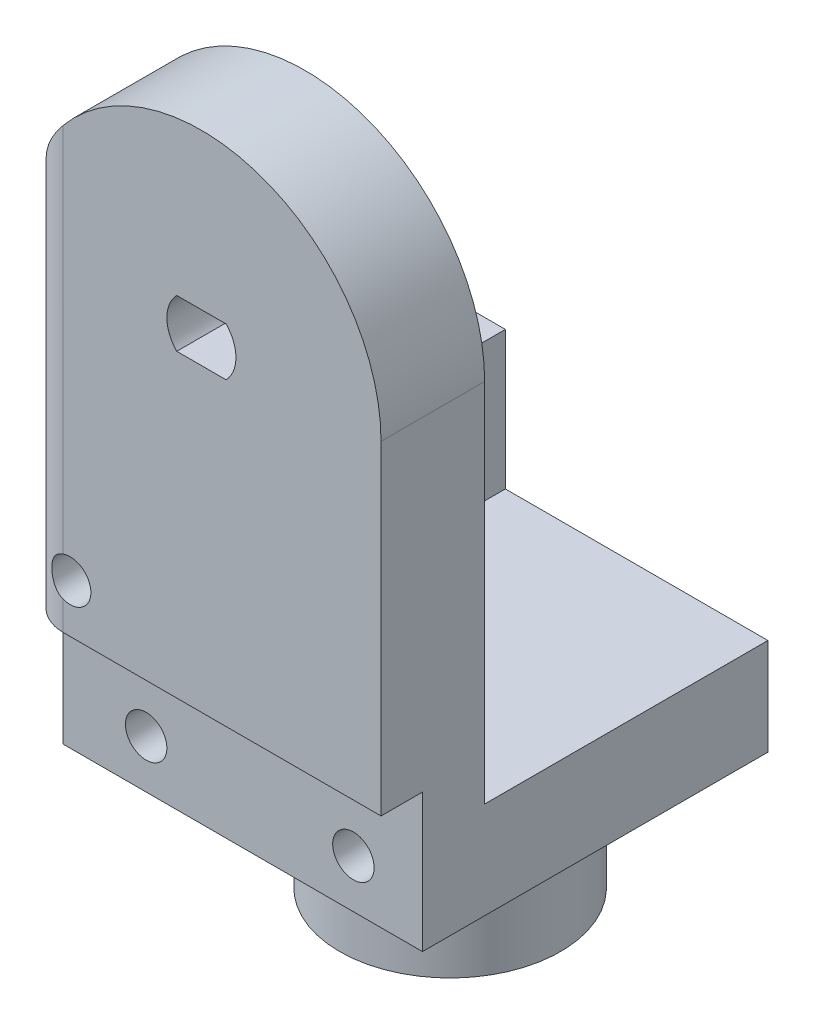
SolidWorks part; units mm, degrees
ref_plane "Front Plane" through (0, 0, 0) normal (0, 0, 1) x (1, 0, 0)
ref_plane "Top Plane" through (0, 0, 0) normal (0, 1, 0) x (1, 0, 0)
ref_plane "Right Plane" through (0, 0, 0) normal (1, 0, 0) x (0, 0, -1)
sketch "Sketch1" plane through (0, 0, 0) normal (0, 0, 1) x (1, 0, 0)
  line L7 (24.2641, -54) -> (50.2641, -54)
  line L9 (24.2641, -4) -> (50.2641, -4)
  line L10 (24.2641, -54) -> (24.2641, -4)
  line L11 (50.2641, -54) -> (50.2641, -4)
  line L14 (39.0495, -22.266) -> (35.4787, -22.266)
  line L15 (35.4787, -18.766) -> (39.0495, -18.766)
  line L16 (37.2641, -4) -> (37.2641, -54) construction
  arc A5 (35.4787, -18.766) -> (35.4787, -22.266) centre (37.2641, -20.516) ccw
  arc A6 (39.0495, -22.266) -> (39.0495, -18.766) centre (37.2641, -20.516) ccw
extrude "Boss-Extrude1" add sketch "Sketch1" along normal blind 8
sketch "Sketch2" plane through (0, 0, -20) normal (0, 0, -1) x (-1, 0, 0)
  line L0 (-39.0495, -18.766) -> (-35.4787, -18.766) construction
  line L1 (-35.4787, -22.266) -> (-39.0495, -22.266) construction
  line L2 (-39.0495, -18.766) -> (-35.4787, -18.766)
  line L3 (-35.4787, -22.266) -> (-39.0495, -22.266)
  line L4 (-50.2641, -4) -> (-50.2641, -54)
  line L5 (-24.2641, -4) -> (-50.2641, -4)
  line L6 (-24.2641, -4) -> (-50.2641, -4)
  line L7 (-50.2641, -4) -> (-50.2641, -54)
  line L9 (-50.2641, -54) -> (-24.2641, -54)
  line L10 (-24.2641, -54) -> (-24.2641, -4)
  line L16 (-50.2641, -54) -> (-24.2641, -54)
  line L17 (-24.2641, -54) -> (-24.2641, -4)
  arc A0 (-39.0495, -18.766) -> (-39.0495, -22.266) centre (-37.2641, -20.516) ccw construction
  arc A1 (-35.4787, -22.266) -> (-35.4787, -18.766) centre (-37.2641, -20.516) ccw construction
  arc A2 (-39.0495, -18.766) -> (-39.0495, -22.266) centre (-37.2641, -20.516) ccw
  arc A3 (-35.4787, -22.266) -> (-35.4787, -18.766) centre (-37.2641, -20.516) ccw
  dimension "D1" = 0
extrude "Boss-Extrude2" add sketch "Sketch2" along normal blind 8 separate body
sketch "Sketch3" plane through (0, 0, 8) normal (0, 0, 1) x (1, 0, 0)
  line L0 (24.2641, -54) -> (50.2641, -54) construction
  line L2 (24.2641, -54) -> (50.2641, -54)
  line L4 (24.2641, -47) -> (50.2641, -47)
  line L6 (50.2641, -47) -> (64.2641, -47) construction
  line L8 (24.2641, -54) -> (24.2641, -47)
  line L10 (50.2641, -54) -> (64.2641, -54) construction
  line L11 (50.2641, -54) -> (50.2641, -4) construction
  line L12 (50.2641, -54) -> (50.2641, -47)
  dimension "D1" = 7
extrude "Boss-Extrude3" add sketch "Sketch3" against normal up to surface (36 mm away) up to face at (37.2641, -29, -28)
sketch "Sketch4" plane through (0, -54, 0) normal (0, -1, 0) x (1, 0, 0)
  line L0 (24.2641, 8) -> (50.2641, 8) construction
  line L1 (37.2641, 8) -> (37.2641, -28) construction
  line L2 (24.2641, -28) -> (50.2641, -28) construction
  line L3 (37.2641, -10) -> (43.8453, -10) construction
  circle A0 centre (37.2641, -10) radius 8
  circle A1 centre (37.2641, -10) radius 5
extrude "Boss-Extrude4" add sketch "Sketch4" along normal blind 10
fillet "Fillet2" radius 3 2 edges at (24.2641, -29, 8) (24.2641, -29, -28)
sketch "Sketch6" plane through (0, 0, -20) normal (0, 0, 1) x (1, 0, 0)
  line L0 (27.2641, -54) -> (50.2641, -54) construction
  line L1 (24.2641, -37) -> (31.2641, -37)
  line L2 (24.2641, -37) -> (24.2641, -54)
  line L3 (24.2641, -54) -> (31.2641, -54)
  line L4 (31.2641, -37) -> (31.2641, -54)
extrude "Boss-Extrude5" add sketch "Sketch6" along normal up to surface (20 mm away) up to face at (37.2641, -25.5, 0)
chamfer "Chamfer1" distance 2 angle 45 1 edges at (37.2641, -54, -2)
sketch "Sketch7" plane through (0, 0, 0) normal (0, 0, -1) x (-1, 0, 0)
  line L6 (-50.2641, -4) -> (-50.2641, -47)
  line L7 (-50.2641, -4) -> (-50.2641, -47)
  line L8 (-50.2641, -47) -> (-31.2641, -47)
  line L9 (-31.2641, -47) -> (-31.2641, -37)
  line L10 (-31.2641, -37) -> (-24.2641, -37)
  line L11 (-31.2641, -37) -> (-24.2641, -37)
  line L12 (-24.2641, -37) -> (-24.2641, -4)
  line L15 (-50.2641, -47) -> (-31.2641, -47)
  line L16 (-31.2641, -47) -> (-31.2641, -37)
  line L21 (-24.2641, -37) -> (-24.2641, -4)
  line L22 (-24.2641, -4) -> (-50.2641, -4)
  line L23 (-24.2641, -4) -> (-50.2641, -4)
  dimension "D1" = 0
extrude "Cut-Extrude2" cut sketch "Sketch7" against normal blind 0.5
sketch "Sketch8" plane through (0, 0, -20) normal (0, 0, 1) x (1, 0, 0)
  line L6 (50.2641, -47) -> (50.2641, -4)
  line L7 (31.2641, -47) -> (50.2641, -47)
  line L8 (50.2641, -47) -> (50.2641, -4)
  line L10 (50.2641, -4) -> (24.2641, -4)
  line L11 (50.2641, -4) -> (24.2641, -4)
  line L12 (24.2641, -4) -> (24.2641, -37)
  line L13 (31.2641, -37) -> (31.2641, -47)
  line L14 (31.2641, -47) -> (50.2641, -47)
  line L20 (31.2641, -37) -> (31.2641, -47)
  line L21 (24.2641, -4) -> (24.2641, -37)
  line L22 (24.2641, -37) -> (31.2641, -37)
  line L23 (24.2641, -37) -> (31.2641, -37)
  dimension "D1" = 0
extrude "Cut-Extrude3" cut sketch "Sketch8" against normal blind 0.5
sketch "Sketch10" plane through (0, 0, 8) normal (0, 0, 1) x (1, 0, 0)
  line L0 (50.2641, -20.516) -> (50.2641, 2.2658)
  line L1 (50.2641, 2.2658) -> (24.2641, 2.2658)
  line L2 (24.2641, 2.2658) -> (24.2641, -20.516)
  arc A0 (50.2641, -20.516) -> (24.2641, -20.516) centre (37.2641, -20.516) ccw
extrude "Cut-Extrude4" cut sketch "Sketch10" against normal up to surface (36 mm away)
sketch "Sketch11" plane through (0, 0, 8) normal (0, 0, 1) x (1, 0, 0)
  line L0 (24.2641, -54) -> (24.2641, -20.516) construction
  line L1 (50.2641, -54) -> (24.2641, -54)
  line L2 (50.2641, -54) -> (50.2641, -44)
  line L3 (50.2641, -44) -> (24.2641, -44)
  line L4 (24.2641, -54) -> (24.2641, -44)
extrude "Cut-Extrude5" cut sketch "Sketch11" against normal blind 3
sketch "Sketch12" plane through (0, 0, -28) normal (0, 0, -1) x (-1, 0, 0)
  line L4 (-50.2641, -44) -> (-50.2641, -54)
  line L5 (-24.2641, -44) -> (-50.2641, -44)
  line L6 (-24.2641, -54) -> (-24.2641, -44)
  line L7 (-50.2641, -54) -> (-24.2641, -54)
  line L8 (-50.2641, -44) -> (-50.2641, -54)
  line L9 (-24.2641, -44) -> (-50.2641, -44)
  line L10 (-24.2641, -54) -> (-24.2641, -44)
  line L11 (-50.2641, -54) -> (-24.2641, -54)
  dimension "D1" = 0
extrude "Cut-Extrude6" cut sketch "Sketch12" against normal blind 3
sketch "Sketch13" plane through (0, 0, 8) normal (0, 0, 1) x (1, 0, 0)
  line L0 (31.2641, -37) -> (31.2641, -47) construction
  line L1 (31.2641, -37) -> (31.2641, -47) construction
  line L2 (31.2641, -37) -> (24.2641, -37) construction
  circle A0 centre (45.2641, -50.5) radius 1.5
  circle A1 centre (30.2641, -50.5) radius 1.5
  circle A2 centre (27.7641, -40.5) radius 1.5
extrude "Cut-Extrude7" cut sketch "Sketch13" against normal up to surface (36 mm away) up to face at (39.4931, -28.1629, -28)
sketch "Sketch14" plane through (0, 0, -28) normal (0, 0, -1) x (-1, 0, 0)
  line L5 (-55.6016, -1.8606) -> (-15.9307, -1.8606)
  line L6 (-55.6016, -1.8606) -> (-55.6016, -72.599)
  line L7 (-55.6016, -72.599) -> (-15.9307, -72.599)
  line L8 (-15.9307, -1.8606) -> (-15.9307, -72.599)
extrude "Cut-Extrude8" cut sketch "Sketch14" against normal blind 8
